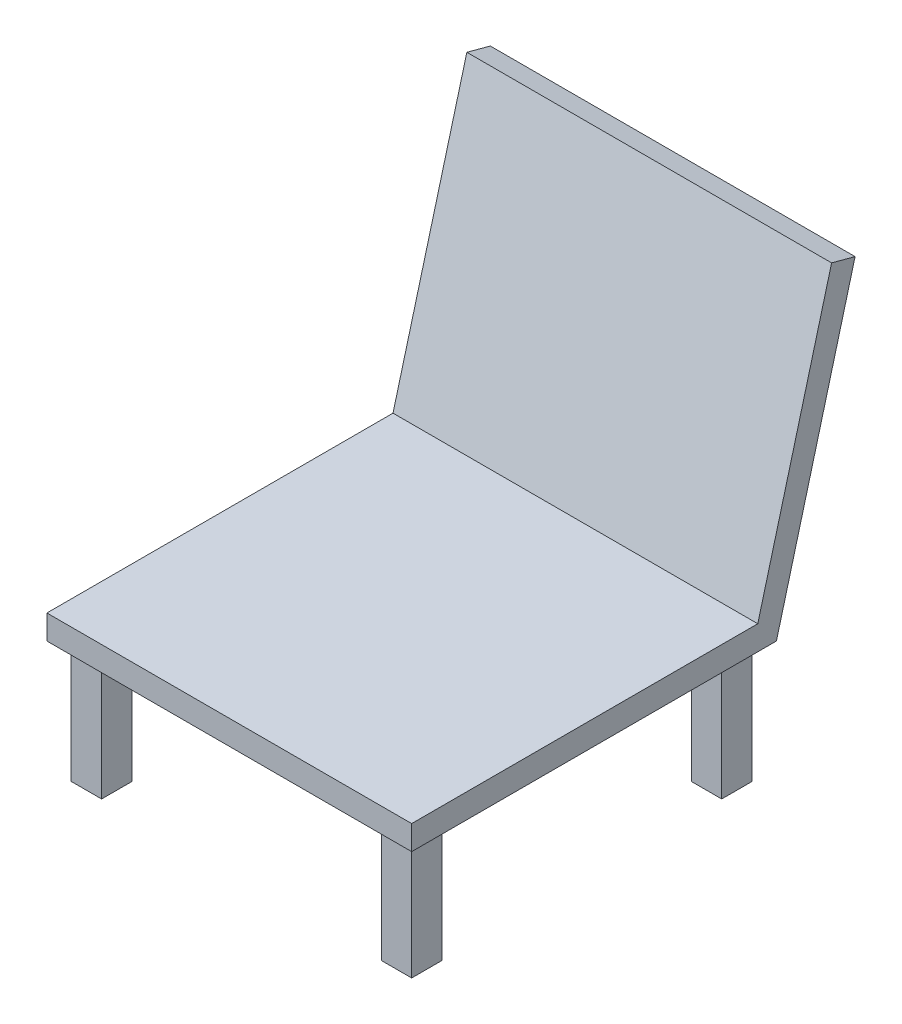
SolidWorks part; units mm, degrees
ref_plane "Front Plane" through (0, 0, 0) normal (0, 0, 1) x (1, 0, 0)
ref_plane "Top Plane" through (0, 0, 0) normal (0, 1, 0) x (1, 0, 0)
ref_plane "Right Plane" through (0, 0, 0) normal (1, 0, 0) x (0, 0, -1)
sketch "Sketch3" plane through (0, 0, 0) normal (1, 0, 0) x (0, 0, -1)
  line L0 (-476.3954, 336.9256) -> (-411.6907, 578.4071)
  line L1 (-491.742, 356.9256) -> (-776.3954, 356.9256)
  line L3 (-476.3954, 336.9256) -> (-776.3954, 336.9256)
  line L4 (-776.3954, 356.9256) -> (-776.3954, 336.9256)
  line L6 (-411.6907, 578.4071) -> (-431.0092, 583.5834)
  line L7 (-491.742, 356.9256) -> (-431.0092, 583.5834)
  dimension "D1" = 300
  dimension "D3" = 250
  dimension "D4" = 20
  dimension "D5" = 105
extrude "Boss-Extrude1" add sketch "Sketch3" along normal blind 300
sketch "Sketch6" plane through (0, 336.9256, 0) normal (0, -1, 0) x (1, 0, 0)
  line L0 (300, 776.3954) -> (0, 776.3954) construction
  line L1 (290, 741.3954) -> (265, 741.3954)
  line L2 (290, 741.3954) -> (290, 766.3954)
  line L3 (290, 766.3954) -> (265, 766.3954)
  line L4 (265, 741.3954) -> (265, 766.3954)
  line L5 (300, 776.3954) -> (300, 476.3954) construction
  line L10 (10, 766.3954) -> (35, 766.3954)
  line L11 (35, 741.3954) -> (35, 766.3954)
  line L12 (10, 741.3954) -> (35, 741.3954)
  line L13 (10, 741.3954) -> (10, 766.3954)
  line L14 (290, 486.3954) -> (265, 486.3954)
  line L15 (265, 511.3954) -> (265, 486.3954)
  line L16 (290, 511.3954) -> (265, 511.3954)
  line L17 (290, 511.3954) -> (290, 486.3954)
  line L18 (10, 511.3954) -> (10, 486.3954)
  line L19 (10, 511.3954) -> (35, 511.3954)
  line L20 (35, 511.3954) -> (35, 486.3954)
  line L21 (10, 486.3954) -> (35, 486.3954)
  point P6 (290, 753.8954)
  dimension "D1" = 25
  dimension "D2" = 25
  dimension "D3" = 10
  dimension "D4" = 10
extrude "Boss-Extrude2" add sketch "Sketch6" along normal blind 100
